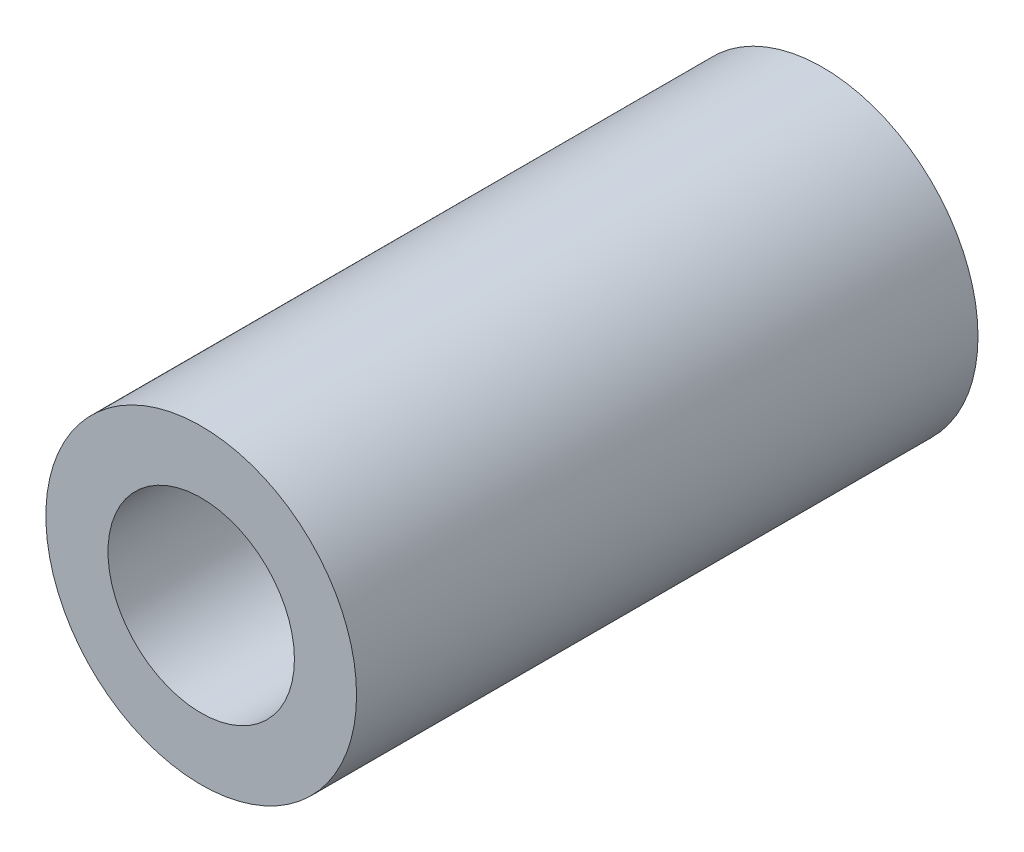
SolidWorks part; units mm, degrees
material "Nylon 101"
ref_plane "Front Plane" through (0, 0, 0) normal (0, 0, 1) x (1, 0, 0)
ref_plane "Top Plane" through (0, 0, 0) normal (0, 1, 0) x (1, 0, 0)
ref_plane "Right Plane" through (0, 0, 0) normal (1, 0, 0) x (0, 0, -1)
sketch "Sketch1" plane through (0, 0, 0) normal (0, 0, 1) x (1, 0, 0)
  circle A0 centre (0, 0) radius 1.5
  circle A1 centre (0, 0) radius 2.5
  dimension "D1" = 3
  dimension "D2" = 1
extrude "Boss-Extrude1" add sketch "Sketch1" along normal blind 10
